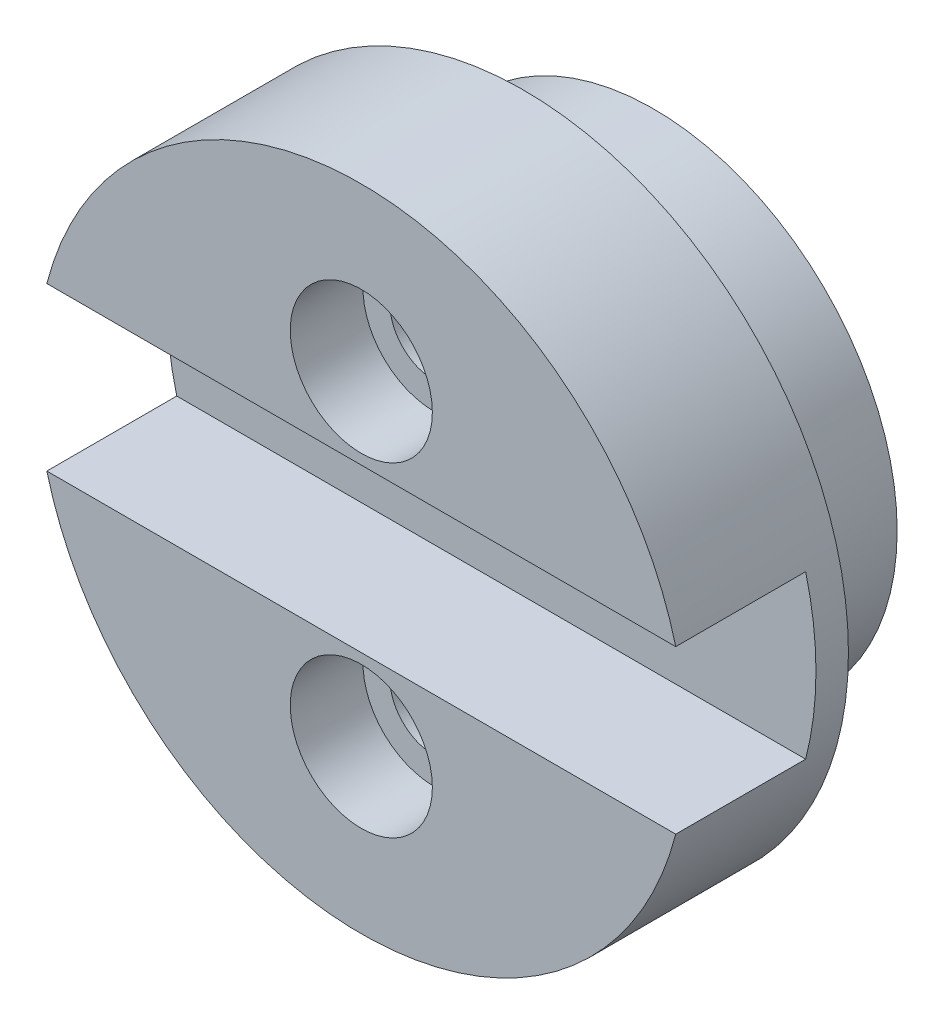
SolidWorks part; units mm, degrees
ref_plane "Front Plane" through (0, 0, 0) normal (0, 0, 1) x (1, 0, 0)
ref_plane "Top Plane" through (0, 0, 0) normal (0, 1, 0) x (1, 0, 0)
ref_plane "Right Plane" through (0, 0, 0) normal (1, 0, 0) x (0, 0, -1)
sketch "Sketch1" plane through (0, 0, 0) normal (0, 0, 1) x (1, 0, 0)
  circle A1 centre (0, 0) radius 9.525
  circle A2 centre (0, 0) radius 9.525
  dimension "D1" = 0
extrude "Boss-Extrude1" add sketch "Sketch1" along normal blind 5.08
sketch "Sketch2" plane through (0, 0, 5.08) normal (0, 0, 1) x (1, 0, 0)
  circle A0 centre (0, 0) radius 12.7
extrude "Boss-Extrude2" add sketch "Sketch2" along normal blind 6.35
sketch "Sketch3" plane through (0, 0, 11.43) normal (0, 0, 1) x (1, 0, 0)
  line L1 (12.7, -3.175) -> (-12.7, -3.175)
  line L2 (12.7, -3.175) -> (12.7, 3.175)
  line L3 (12.7, 3.175) -> (-12.7, 3.175)
  line L4 (-12.7, -3.175) -> (-12.7, 3.175)
  line L5 (12.7, -3.175) -> (-12.7, 3.175) construction
  line L6 (12.7, 3.175) -> (-12.7, -3.175) construction
  point P0 (0, 0)
  dimension "D1" = 6.35
extrude "Cut-Extrude1" cut sketch "Sketch3" against normal blind 5.08
hole_wizard "CBORE for #4 Socket Head Cap Screw1" positions "Sketch5" profile "Sketch4" counterbore size "#4" standard "ANSI Inch" end condition through all
sketch "Sketch5" plane through (0, 0, 11.43) normal (0, 0, 1) x (1, 0, 0)
  circle A0 centre (0, 0) radius 9.525 construction
  circle A1 centre (0, 0) radius 9.525
  circle A2 centre (0, 0) radius 3.175
  circle A4 centre (0, 0) radius 6.35
  point P4 (0, -6.35)
  point P15 (0, 6.35)
  dimension "D1" = 6.35
  dimension "D2" = 19.05
sketch "Sketch4" plane through (0, -6.35, 11.43) normal (1, 0, 0) x (0, -1, 0)
  line L0 (0, 0) -> (0, 11.43)
  line L1 (0, 11.43) -> (1.7272, 11.43)
  line L3 (1.7272, 11.43) -> (1.7272, 2.8448)
  line L4 (1.7272, 2.8448) -> (2.7788, 2.8448)
  line L5 (2.7788, 2.8448) -> (2.7788, 0)
  line L7 (2.7788, 0) -> (0, 0)
  line L11 (0, -6.35) -> (0, 107.95) construction
  dimension "Thru Hole Dia." = 3.4544
  dimension "Thru Hole Depth" = 11.43
  dimension "C'Bore Dia." = 5.5575
  dimension "C'Bore Depth" = 2.8448
